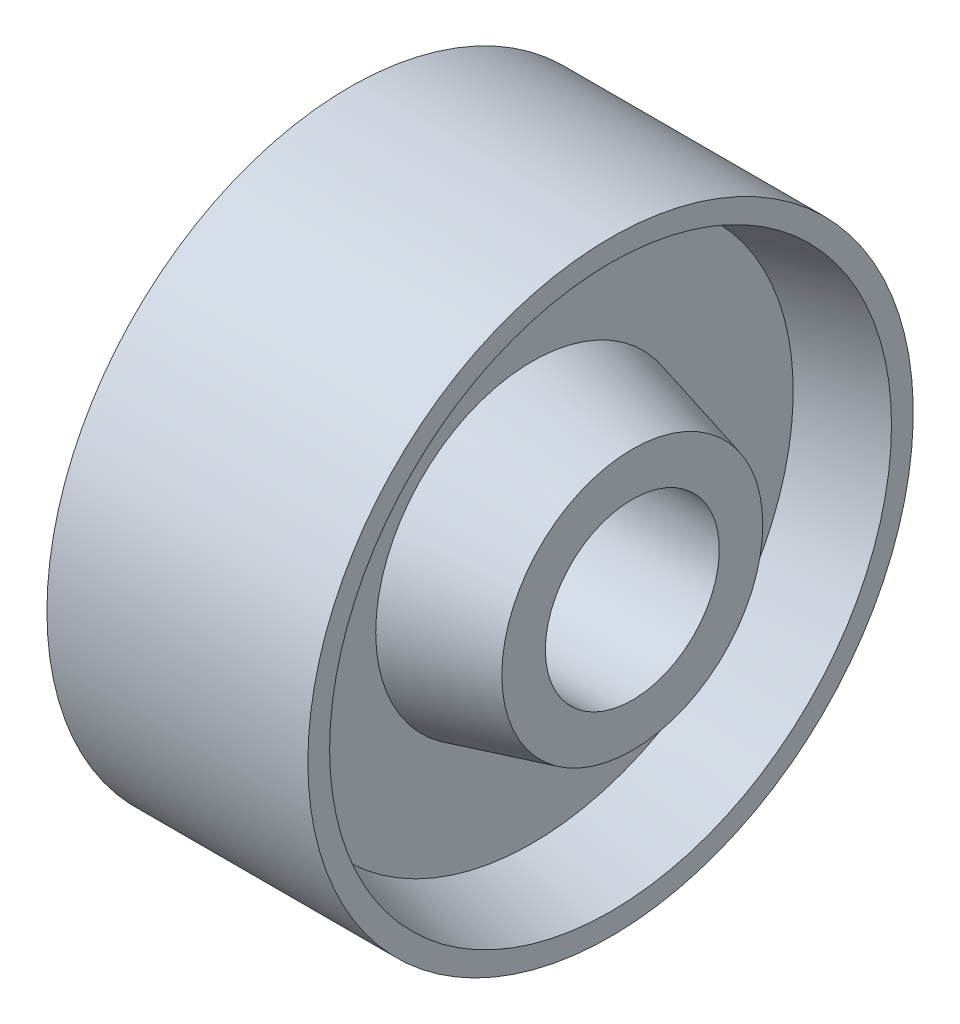
SolidWorks part; units mm, degrees
ref_plane "Front Plane" through (0, 0, 0) normal (0, 0, 1) x (1, 0, 0)
ref_plane "Top Plane" through (0, 0, 0) normal (0, 1, 0) x (1, 0, 0)
ref_plane "Right Plane" through (0, 0, 0) normal (1, 0, 0) x (0, 0, -1)
sketch "Sketch1" plane through (0, 0, 0) normal (0, 0, 1) x (1, 0, 0)
  line L0 (0, -61.1697) -> (0, 61.1697) construction
  line L1 (-95.5413, 0) -> (95.5413, 0) construction
  line L2 (-22.225, 12.7) -> (22.225, 12.7)
  line L3 (22.225, 12.7) -> (22.225, 19.05)
  line L4 (22.225, 19.05) -> (7.62, 22.86)
  line L5 (7.62, 22.86) -> (7.62, 38.1)
  line L6 (7.62, 38.1) -> (19.05, 41.021)
  line L7 (19.05, 41.021) -> (19.05, 44.196)
  line L8 (19.05, 44.196) -> (-19.05, 44.196)
  line L9 (-19.05, 44.196) -> (-19.05, 41.021)
  line L10 (-19.05, 41.021) -> (-7.62, 38.1)
  line L11 (-7.62, 38.1) -> (-7.62, 22.86)
  line L12 (-7.62, 22.86) -> (-22.225, 19.05)
  line L13 (-22.225, 19.05) -> (-22.225, 12.7)
  point P8 (0, 0)
  point P18 (0, 0)
  point P19 (0, 0)
  point P20 (0, 0)
  point P21 (19.05, 40.6633)
  dimension "D1" = 25.4
  dimension "D2" = 44.45
  dimension "D3" = 38.1
  dimension "D4" = 38.1
  dimension "D5" = 15.24
  dimension "D6" = 45.72
  dimension "D7" = 88.392
  dimension "D8" = 76.2
  dimension "D9" = 3.175
revolve "Revolve1" add sketch "Sketch1" angle 360 about L1
